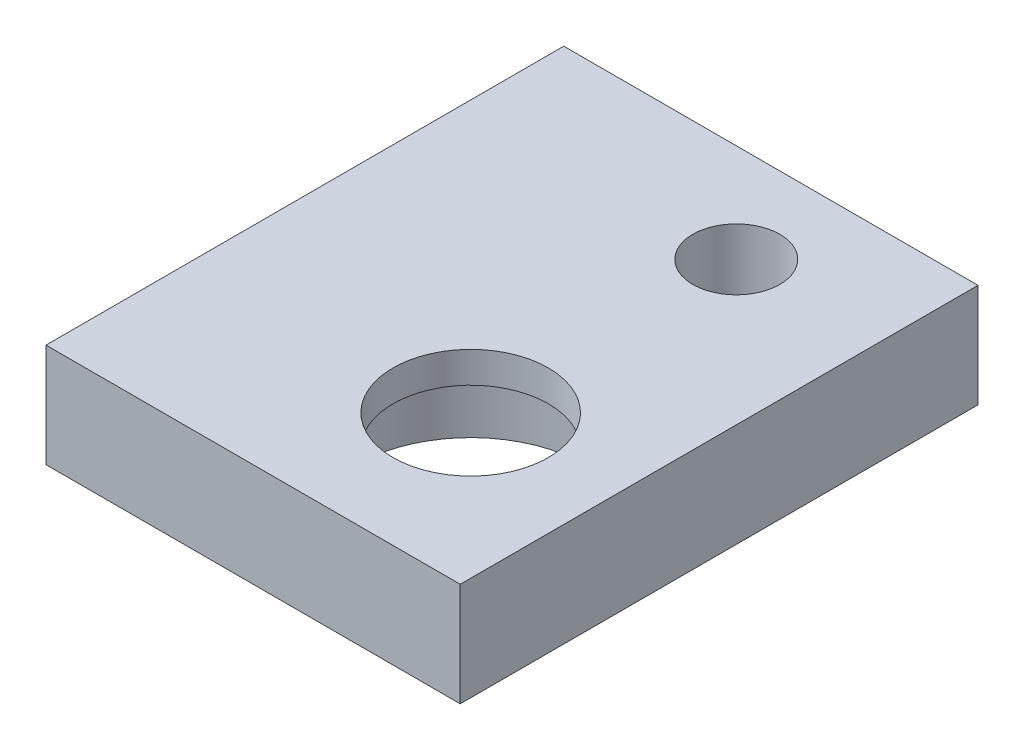
SolidWorks part; units mm, degrees
ref_plane "Front Plane" through (0, 0, 0) normal (0, 0, 1) x (1, 0, 0)
ref_plane "Top Plane" through (0, 0, 0) normal (0, 1, 0) x (1, 0, 0)
ref_plane "Right Plane" through (0, 0, 0) normal (1, 0, 0) x (0, 0, -1)
sketch "Sketch2" plane through (0, 0, 0) normal (0, 1, 0) x (1, 0, 0)
  line L0 (26.16, -35.15) -> (26.16, -9.5) construction
  line L1 (0, 0) -> (40, 0)
  line L2 (0, 0) -> (0, -50)
  line L3 (0, -50) -> (40, -50)
  line L4 (40, 0) -> (40, -50)
  circle A0 centre (26.16, -9.5) radius 4.2
  circle A1 centre (26.16, -35.15) radius 11.2
  circle A9 centre (26.16, -35.15) radius 7.5
  dimension "D3" = 26.16
  dimension "D4" = 9.5
  dimension "D5" = 14.85
  dimension "D6" = 22.4
  dimension "D7" = 15
  dimension "D8" = 8.4
  dimension "D1" = 50
  dimension "D2" = 40
extrude "Boss-Extrude1" add sketch "Sketch2" along normal blind 10 contours L2 L3 L4 L1
sketch "Sketch3" plane through (0, 0, 0) normal (0, -1, 0) x (1, 0, 0)
  line L4 (0, 0) -> (40, 0)
  line L5 (40, 0) -> (40, 50)
  line L6 (40, 50) -> (0, 50)
  line L7 (0, 50) -> (0, 0)
  line L8 (0, 0) -> (40, 0)
  line L9 (40, 0) -> (40, 50)
  line L10 (40, 50) -> (0, 50)
  line L11 (0, 50) -> (0, 0)
  circle A0 centre (26.16, 35.15) radius 11.2 construction
  circle A1 centre (26.16, 35.15) radius 7.5 construction
  circle A2 centre (26.16, 35.15) radius 11.2
  circle A3 centre (26.16, 35.15) radius 7.5
  dimension "D1" = 0
extrude "Cut-Extrude1" cut sketch "Sketch3" against normal blind 7 contours A2 A3 | A3
sketch "Sketch4" plane through (0, 0, 0) normal (0, -1, 0) x (1, 0, 0)
  circle A0 centre (26.16, 35.15) radius 7.5 construction
  circle A1 centre (26.16, 9.5) radius 4.2 construction
  circle A2 centre (26.16, 35.15) radius 7.5
  circle A3 centre (26.16, 9.5) radius 4.2
extrude "Cut-Extrude2" cut sketch "Sketch4" against normal through all
